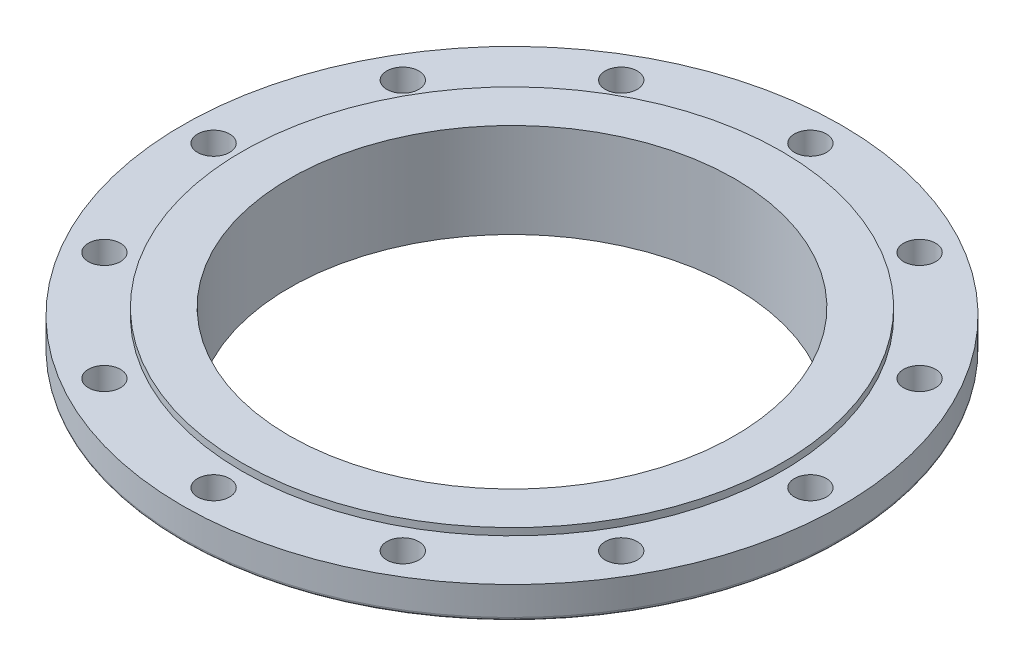
SolidWorks part; units mm, degrees
material " 12Х18Н10Т ГОСТ 4543-71"
ref_plane "Спереди" through (0, 0, 0) normal (0, 0, 1) x (1, 0, 0)
ref_plane "Сверху" through (0, 0, 0) normal (0, 1, 0) x (1, 0, 0)
ref_plane "Справа" through (0, 0, 0) normal (1, 0, 0) x (0, 0, -1)
sketch "Эскиз1" plane through (0, 0, 0) normal (0, 0, 1) x (1, 0, 0)
  line L0 (0, 0) -> (0, 60.5833) construction
  line L1 (-125, 0) -> (-125, 53)
  line L2 (-151.5, 49) -> (-151.5, 53)
  line L3 (-151.5, 53) -> (-125, 53)
  line L6 (-151.5, 49) -> (-185, 49)
  line L7 (-185, 49) -> (-185, 33)
  line L8 (-183, 31) -> (-149.9614, 31)
  line L9 (-143.0507, 25.1146) -> (-139, 0)
  line L10 (-139, 0) -> (-125, 0)
  arc A0 (-143.0507, 25.1146) -> (-149.9614, 31) centre (-149.9614, 24) ccw
  arc A1 (-185, 33) -> (-183, 31) centre (-183, 33) ccw
  point P15 (-144, 31)
  dimension "D12" = 7
  dimension "D13" = 2
  dimension "D1" = 370
  dimension "D2" = 250
  dimension "D3" = 278
  dimension "D4" = 288
  dimension "D5" = 53
  dimension "D6" = 303
  dimension "D7" = 4
  dimension "D8" = 18
revolve "Повернуть1" add sketch "Эскиз1" angle 360 about L0
sketch "Эскиз2" plane through (0, 49, 0) normal (0, 1, 0) x (1, 0, 0)
  circle A0 centre (0, 0) radius 167.5 construction
  circle A1 centre (-167.5, 0) radius 9
  circle A2 centre (-145.0593, 83.75) radius 9
  circle A3 centre (-83.75, 145.0593) radius 9
  circle A4 centre (0, 167.5) radius 9
  circle A5 centre (83.75, 145.0593) radius 9
  circle A6 centre (145.0593, 83.75) radius 9
  circle A7 centre (167.5, 0) radius 9
  circle A8 centre (145.0593, -83.75) radius 9
  circle A9 centre (83.75, -145.0593) radius 9
  circle A10 centre (0, -167.5) radius 9
  circle A11 centre (-83.75, -145.0593) radius 9
  circle A12 centre (-145.0593, -83.75) radius 9
  point P14 (0, 0)
  dimension "D1" = 335
  dimension "D2" = 18
  dimension "D3" = 12
extrude "Вырез-Вытянуть1" cut sketch "Эскиз2" against normal through all
